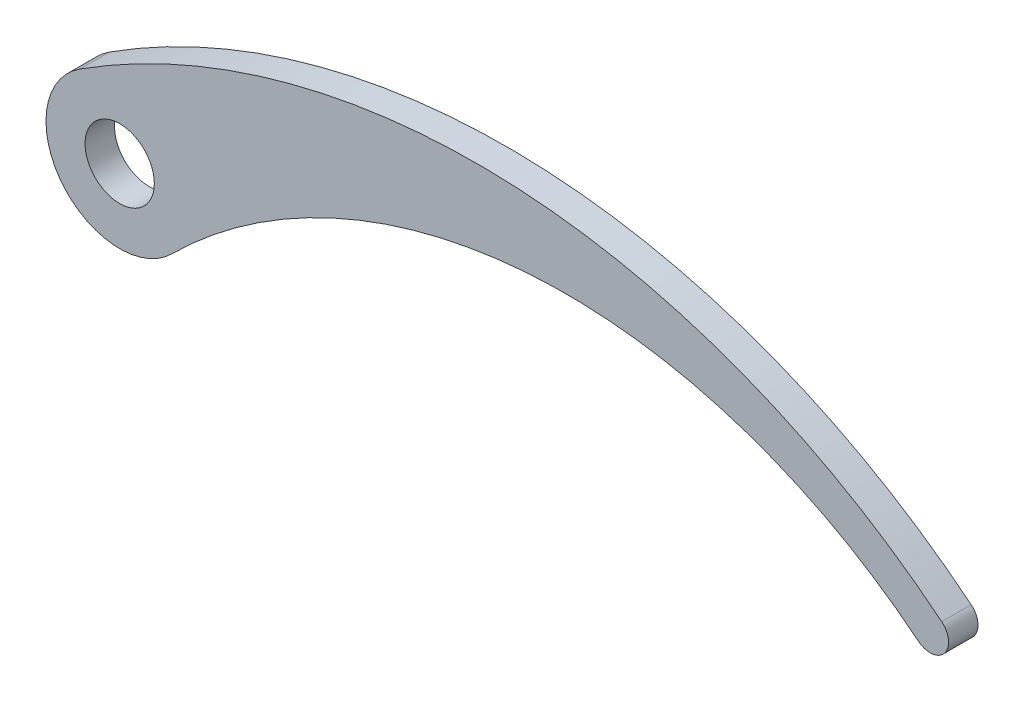
SolidWorks part; units mm, degrees
ref_plane "Front Plane" through (0, 0, 0) normal (0, 0, 1) x (1, 0, 0)
ref_plane "Top Plane" through (0, 0, 0) normal (0, 1, 0) x (1, 0, 0)
ref_plane "Right Plane" through (0, 0, 0) normal (1, 0, 0) x (0, 0, -1)
sketch "Sketch1" plane through (0, 0, 0) normal (0, 0, 1) x (1, 0, 0)
  line L0 (-10.7179, 0) -> (69.4329, 0) construction
  line L1 (55, 9.3211) -> (55, -10.0077) construction
  circle A0 centre (0, 0) radius 2.35
  arc A1 (-2.7004, 4.208) -> (3.5237, -3.5473) centre (0, 0) ccw
  arc A2 (54.2135, -0.9716) -> (55.7871, 0.9711) centre (55, 0) ccw
  arc A3 (-2.7004, 4.208) -> (55.7871, 0.9711) centre (24.304, -37.8724) cw
  arc A4 (3.5237, -3.5473) -> (54.2135, -0.9716) centre (30.304, -30.5069) cw
  point P16 (0, 0)
  dimension "D1" = 4.7
  dimension "D2" = 10
  dimension "D4" = 2.5
  dimension "D5" = 50
  dimension "D6" = 38
  dimension "D3" = 55
extrude "Boss-Extrude1" add sketch "Sketch1" along normal blind 2
